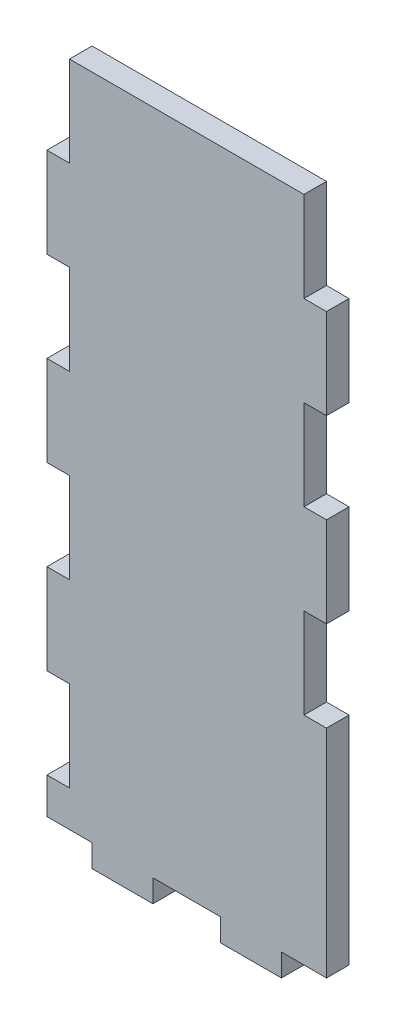
SolidWorks part; units mm, degrees
ref_plane "Front Plane" through (0, 0, 0) normal (0, 0, 1) x (1, 0, 0)
ref_plane "Top Plane" through (0, 0, 0) normal (0, 1, 0) x (1, 0, 0)
ref_plane "Right Plane" through (0, 0, 0) normal (1, 0, 0) x (0, 0, -1)
sketch "Sketch2" plane through (0, 0, 0) normal (0, 0, 1) x (1, 0, 0)
  line L0 (9.525, -93.98) -> (9.525, -100.33)
  line L1 (-39.37, 93.98) -> (39.37, 93.98)
  line L2 (-39.37, 93.98) -> (-39.37, -93.98)
  line L3 (-39.37, -93.98) -> (39.37, -93.98)
  line L4 (39.37, 93.98) -> (39.37, -93.98)
  line L5 (-26.67, -93.98) -> (-9.525, -93.98)
  line L6 (-26.67, -93.98) -> (-26.67, -100.33)
  line L7 (-26.67, -100.33) -> (-9.525, -100.33)
  line L8 (-9.525, -93.98) -> (-9.525, -100.33)
  line L9 (9.525, -100.33) -> (26.67, -100.33)
  line L10 (26.67, -93.98) -> (26.67, -100.33)
  line L11 (-26.67, -93.98) -> (9.525, -93.98) construction
  line L12 (-39.37, 68.58) -> (-33.02, 68.58)
  line L13 (-39.37, 93.98) -> (-33.02, 93.98)
  line L14 (-39.37, 93.98) -> (-39.37, -93.98)
  line L15 (-39.37, -93.98) -> (-33.02, -93.98)
  line L16 (-33.02, 93.98) -> (-33.02, -93.98)
  line L17 (-39.37, 43.18) -> (-33.02, 43.18)
  line L18 (-39.37, 17.78) -> (-33.02, 17.78)
  line L19 (-39.37, -7.62) -> (-33.02, -7.62)
  line L20 (-39.37, -33.02) -> (-33.02, -33.02)
  line L21 (-39.37, -58.42) -> (-33.02, -58.42)
  line L22 (-39.37, -83.82) -> (-33.02, -83.82)
  line L23 (-39.37, 68.58) -> (-39.37, 43.18) construction
  line L24 (33.02, 68.58) -> (39.37, 68.58)
  line L25 (39.37, 93.98) -> (33.02, 93.98)
  line L26 (39.37, 93.98) -> (39.37, -93.98)
  line L27 (39.37, -93.98) -> (33.02, -93.98)
  line L28 (33.02, 93.98) -> (33.02, -93.98)
  line L29 (33.02, 43.18) -> (39.37, 43.18)
  line L30 (33.02, 17.78) -> (39.37, 17.78)
  line L31 (33.02, -7.62) -> (39.37, -7.62)
  line L32 (33.02, -33.02) -> (39.37, -33.02)
  line L33 (33.02, 68.58) -> (33.02, 43.18) construction
  point P4 (0, 93.98)
  point P6 (39.37, 0)
  dimension "D1" = 187.96
  dimension "D2" = 78.74
  dimension "D3" = 6.35
  dimension "D4" = 12.7
  dimension "D5" = 17.145
  dimension "D7" = 36.195
  dimension "D8" = 6.35
  dimension "D9" = 25.4
  dimension "D11" = 25.4
  dimension "D12" = 6.35
  dimension "D13" = 25.4
  dimension "D15" = 25.4
  dimension "D6" = 2
  dimension "D10" = 7
  dimension "D14" = 5
extrude "Boss-Extrude1" add sketch "Sketch2" along normal blind 6.35 contours L4 L1 L2 L3 | L8 L3 L6 L7 | L10 L3 L0 L9 | L2 L17 L16 L12 | L2 L19 L16 L18 | L2 L21 L16 L20 | L22 L2 L3 L16 | L28 L29 L4 L24 | L28 L31 L4 L30 | L32 L28 L3 L4
